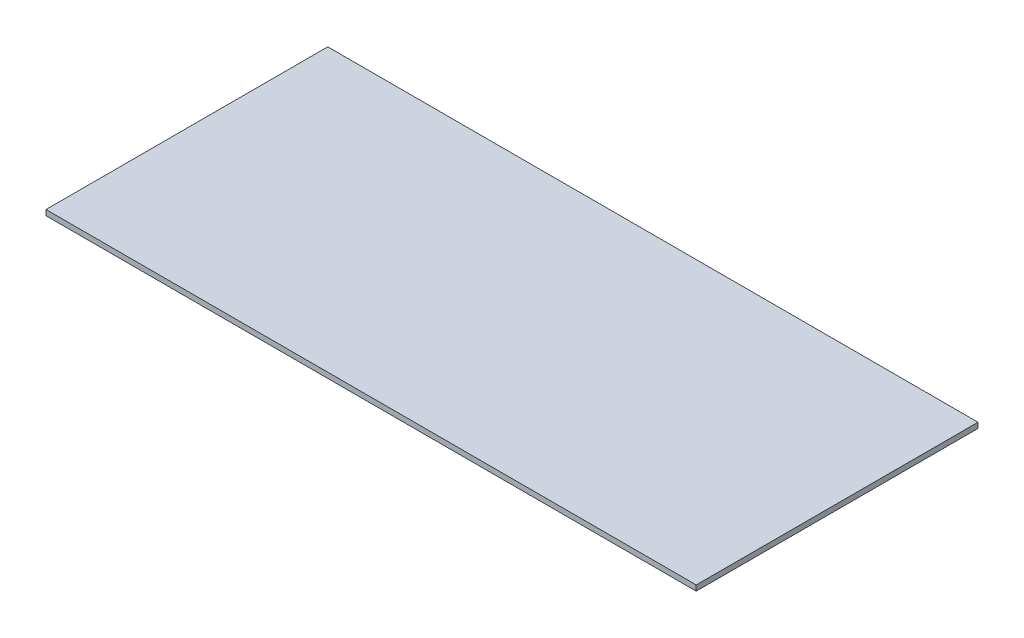
SolidWorks part; units mm, degrees
material "Acrylic (Medium-high impact)"
ref_plane "Front" through (0, 0, 0) normal (0, 0, 1) x (1, 0, 0)
ref_plane "Top" through (0, 0, 0) normal (0, 1, 0) x (1, 0, 0)
ref_plane "Right" through (0, 0, 0) normal (1, 0, 0) x (0, 0, -1)
sketch "Sketch1" plane through (0, 0, 0) normal (0, 1, 0) x (1, 0, 0)
  line L1 (-190.5, -82.55) -> (190.5, -82.55)
  line L2 (-190.5, -82.55) -> (-190.5, 82.55)
  line L3 (-190.5, 82.55) -> (190.5, 82.55)
  line L4 (190.5, -82.55) -> (190.5, 82.55)
  line L5 (-190.5, -82.55) -> (190.5, 82.55) construction
  line L6 (-190.5, 82.55) -> (190.5, -82.55) construction
  point P0 (0, 0)
  dimension "D1" = 165.1
  dimension "D2" = 381
extrude "Boss-Extrude1" add sketch "Sketch1" along normal blind 3.175
